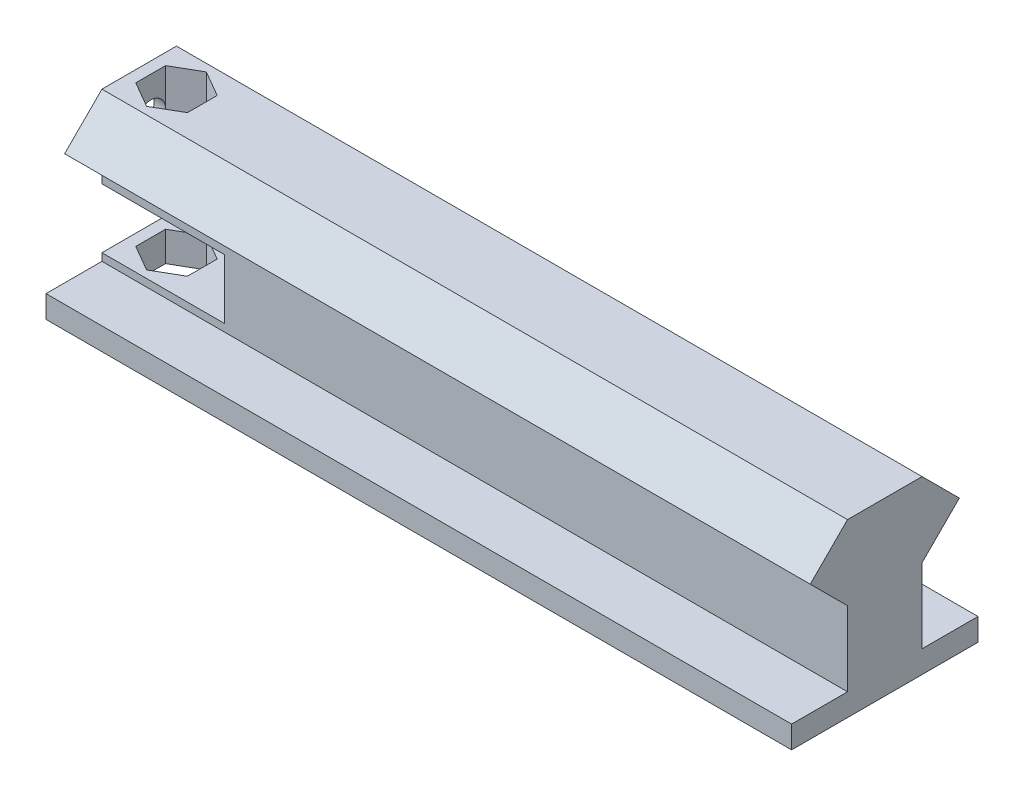
SolidWorks part; units mm, degrees
ref_plane "Front Plane" through (0, 0, 0) normal (0, 0, 1) x (1, 0, 0)
ref_plane "Top Plane" through (0, 0, 0) normal (0, 1, 0) x (1, 0, 0)
ref_plane "Right Plane" through (0, 0, 0) normal (1, 0, 0) x (0, 0, -1)
sketch "Sketch1" plane through (0, 0, 0) normal (1, 0, 0) x (0, 0, -1)
  line L0 (5, 5) -> (10, 10)
  line L1 (-5, 5) -> (5, 5) construction
  line L2 (-5, 5) -> (-5, -5)
  line L3 (-5, -5) -> (5, -5) construction
  line L4 (5, 5) -> (5, -5)
  line L5 (-5, 5) -> (5, -5) construction
  line L6 (-5, -5) -> (5, 5) construction
  line L7 (10, 10) -> (5, 15)
  line L8 (5, 15) -> (-5, 15)
  line L9 (-5, 15) -> (-10, 10)
  line L10 (-10, 10) -> (-5, 5)
  line L11 (5, -5) -> (12.5, -5)
  line L12 (12.5, -5) -> (12.5, -8)
  line L13 (-5, -5) -> (-12.5, -5)
  line L14 (-12.5, -5) -> (-12.5, -8)
  line L15 (-12.5, -8) -> (12.5, -8)
  point P0 (0, 0)
  dimension "D1" = 10
  dimension "D2" = 10
  dimension "D3" = 7.5
  dimension "D4" = 3
  dimension "D5" = 7.5
extrude "Boss-Extrude1" add sketch "Sketch1" along normal mid plane 100
sketch "Sketch2" plane through (0, 0, 0) normal (0, 1, 0) x (1, 0, 0)
  line L0 (0, 0) -> (-45, 0) construction
  circle A0 centre (-45, 0) radius 12.5
  circle A1 centre (-45, 0) radius 4
  dimension "D2" = 25
  dimension "D3" = 8
  dimension "D1" = 45
extrude "Cut-Extrude1" cut sketch "Sketch2" against normal mid plane 8
sketch "Sketch4" plane through (0, 0, 0) normal (0, 1, 0) x (1, 0, 0)
  line L0 (0, 0) -> (-45, 0) construction
  line L2 (-45, -4) -> (-41.5359, -2)
  line L3 (-41.5359, -2) -> (-41.5359, 2)
  line L4 (-41.5359, 2) -> (-45, 4)
  line L5 (-45, 4) -> (-48.4641, 2)
  line L6 (-48.4641, 2) -> (-48.4641, -2)
  line L7 (-48.4641, -2) -> (-45, -4)
  circle A0 centre (-45, 0) radius 4 construction
  dimension "D2" = 8
  dimension "D1" = 45
extrude "Cut-Extrude3" cut sketch "Sketch4" against normal through all both and the other way through all
sketch "Sketch6" plane through (-50, 0, 0) normal (-1, 0, 0) x (0, 0, 1)
  line L0 (0, 15) -> (0, 10) construction
  line L1 (-5, 15) -> (5, 15) construction
  circle A0 centre (0, 10) radius 2
  dimension "D2" = 4
  dimension "D1" = 5
extrude "Cut-Extrude4" cut sketch "Sketch6" against normal blind 4
